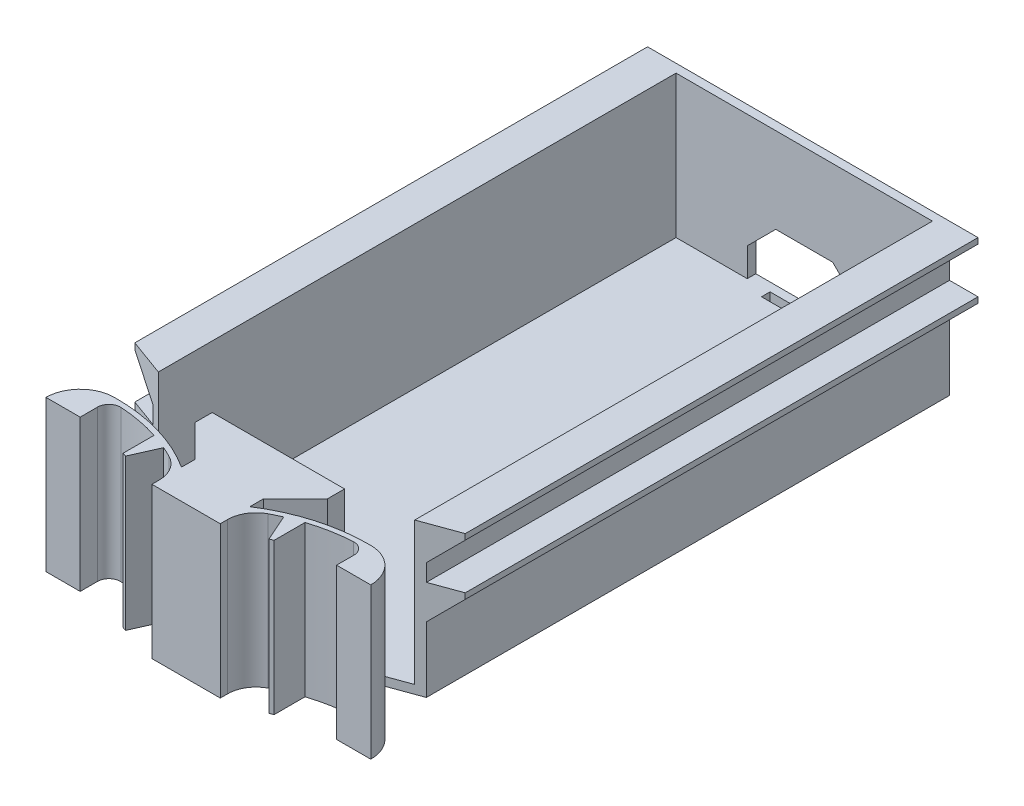
SolidWorks part; units mm, degrees
ref_plane "Plano frontal" through (0, 0, 0) normal (0, 0, 1) x (1, 0, 0)
ref_plane "Plano superior" through (0, 0, 0) normal (0, 1, 0) x (1, 0, 0)
ref_plane "Plano direito" through (0, 0, 0) normal (1, 0, 0) x (0, 0, -1)
sketch "Esboço1" plane through (0, 0, 0) normal (0, 0, 1) x (1, 0, 0)
  line L0 (-24, 14) -> (-24, -14) construction
  line L1 (24, 14) -> (24, -14) construction
  line L2 (-22.5, 12.5) -> (-22.5, -12.5)
  line L3 (-22.5, -12.5) -> (22.5, -12.5)
  line L4 (22.5, 12.5) -> (22.5, -12.5)
  line L5 (-22.5, 12.5) -> (22.5, -12.5) construction
  line L6 (-22.5, -12.5) -> (22.5, 12.5) construction
  line L7 (24, 12.5) -> (24, -14)
  line L8 (-24, -14) -> (24, -14)
  line L9 (-24, 12.5) -> (-24, -14)
  line L10 (-22.5, 12.5) -> (-24, 12.5)
  line L11 (22.5, 12.5) -> (24, 12.5)
  line L13 (-22.5, 12.5) -> (22.5, 12.5) construction
  line L14 (-24, 14) -> (24, 14) construction
  point P0 (0, 0)
  dimension "D1" = 25
  dimension "D2" = 45
  dimension "D3" = 1.5
extrude "Ressalto-extrusão1" add sketch "Esboço1" along normal blind 100
sketch "Esboço2" plane through (0, 0, 0) normal (0, 0, -1) x (-1, 0, 0)
  line L0 (-24, 12.5) -> (-29, 12.5)
  line L1 (-29, 11.5) -> (-24, 6.5)
  line L2 (-24, 12.5) -> (-24, 6.5)
  line L3 (-24, 6.5) -> (-24, 3.5) construction
  line L4 (-24, -14) -> (-24, 12.5) construction
  line L5 (-24, 3.5) -> (-29, 3.5)
  line L6 (-29, 2.5) -> (-24, -2.5)
  line L7 (-24, 3.5) -> (-24, -2.5)
  line L8 (0, -12.5) -> (0, 0) construction
  line L9 (-22.5, -12.5) -> (22.5, -12.5) construction
  line L10 (-24, 12.5) -> (-29, 12.5) construction
  line L11 (-29, 12.5) -> (-29, 11.5)
  line L12 (-29, 3.5) -> (-29, 2.5)
  line L13 (24, 12.5) -> (29, 12.5) construction
  line L14 (24, 6.5) -> (24, 3.5) construction
  line L15 (29, 3.5) -> (29, 2.5)
  line L16 (29, 12.5) -> (29, 11.5)
  line L17 (24, 3.5) -> (24, -2.5)
  line L18 (29, 2.5) -> (24, -2.5)
  line L19 (24, 3.5) -> (29, 3.5)
  line L20 (24, 12.5) -> (24, 6.5)
  line L21 (29, 11.5) -> (24, 6.5)
  line L22 (24, 12.5) -> (29, 12.5)
  dimension "D2" = 6
  dimension "D3" = 3
  dimension "D5" = 6
extrude "Ressalto-extrusão2" add sketch "Esboço2" against normal up to surface (100 mm away) up to face at (0, -0.375, 100)
sketch "Esboço3" plane through (0, -12.5, 0) normal (0, 1, 0) x (1, 0, 0)
  line L0 (22.5, -100) -> (22.5, 0) construction
  line L1 (-22.5, 0) -> (22.5, 0)
  line L2 (-22.5, 0) -> (-22.5, -1.5)
  line L3 (-22.5, -1.5) -> (22.5, -1.5)
  line L4 (22.5, 0) -> (22.5, -1.5)
  dimension "D1" = 1.5
extrude "Ressalto-extrusão3" add sketch "Esboço3" along normal up to surface (25 mm away) up to face at (-25.75, 12.5, 50)
sketch "Esboço4" plane through (0, 0, 1.5) normal (0, 0, 1) x (1, 0, 0)
  line L0 (22.5, -12.5) -> (-22.5, -12.5) construction
  line L1 (-10, -12.5) -> (10, -12.5)
  line L2 (-10, -12.5) -> (-10, -7.5)
  line L3 (-5, -2.5) -> (5, -2.5)
  line L4 (10, -12.5) -> (10, -7.5)
  line L5 (-10, -7.5) -> (-5, -2.5)
  line L6 (5, -2.5) -> (10, -7.5)
  point P1 (10, -2.5)
  point P2 (-10, -2.5)
  point P4 (0, -12.5)
  point P5 (0, -12.5)
extrude "Corte-extrusão1" cut sketch "Esboço4" against normal through all
sketch "Esboço5" plane through (0, -12.5, 0) normal (0, 1, 0) x (1, 0, 0)
  line L0 (0, 0) -> (0, -2.25) construction
  line L1 (22.5, -1.5) -> (-22.5, -1.5) construction
  line L2 (-6, -3) -> (6, -3)
  line L3 (-6, -3) -> (-6, -1.5)
  line L4 (-6, -1.5) -> (6, -1.5)
  line L5 (6, -3) -> (6, -1.5)
  line L6 (-6, -3) -> (6, -1.5) construction
  line L7 (-6, -1.5) -> (6, -3) construction
  dimension "D1" = 2.25
  dimension "D2" = 12
extrude "Corte-extrusão2" cut sketch "Esboço5" against normal through all
sketch "Esboço9" plane through (0, -14, 0) normal (0, -1, 0) x (1, 0, 0)
  line L0 (-12.5151, 96) -> (-29, 90)
  line L1 (29, 100) -> (29, 0) construction
  line L2 (29, 100) -> (29, 90)
  line L3 (29, 100) -> (12.5151, 100)
  line L4 (0, 100) -> (0, 80.1463) construction
  line L5 (-24, 100) -> (24, 100) construction
  line L6 (12.5151, 100) -> (12.5151, 96)
  line L7 (12.5151, 96) -> (29, 90)
  line L8 (-12.5151, 100) -> (-12.5151, 96)
  line L9 (-29, 100) -> (-12.5151, 100)
  line L10 (-29, 100) -> (-29, 90)
extrude "Corte-extrusão3" cut sketch "Esboço9" against normal through all
sketch "Esboço6" plane through (0, -14, 0) normal (0, -1, 0) x (1, 0, 0)
  line L0 (0, 93.7975) -> (0, 110) construction
  line L1 (-6, 110) -> (6, 110)
  line L2 (-11.6169, 93.7975) -> (11.6169, 93.7975)
  line L3 (6, 102.4144) -> (11.6169, 96.7975)
  line L4 (-22.5012, 106.0843) -> (-28.5012, 106.0843)
  line L5 (-22.5032, 103.0315) -> (-22.5012, 106.0843)
  line L6 (-22.5012, 105.1843) -> (-27.5212, 105.1843) construction
  line L7 (11.6169, 96.7975) -> (11.6169, 93.7975)
  line L8 (-6, 104.8102) -> (-6, 102.4144)
  line L9 (13.2473, 107.8029) -> (13.2473, 102.372)
  line L10 (12.6005, 108.0363) -> (10.5387, 103.397)
  line L11 (12.6005, 108.0363) -> (13.2473, 107.8029)
  line L12 (6, 110) -> (6, 108.7188)
  line L13 (6, 104.8102) -> (6, 102.4144)
  line L14 (-6, 110) -> (-6, 108.7188)
  line L15 (-12.6005, 108.0363) -> (-13.2473, 107.8029)
  line L16 (-12.6005, 108.0363) -> (-10.5387, 103.397)
  line L17 (-13.2473, 107.8029) -> (-13.2473, 102.372)
  line L18 (22.5032, 103.0315) -> (22.5012, 106.0843)
  line L19 (22.5012, 106.0843) -> (28.5012, 106.0843)
  line L26 (-11.6169, 96.7975) -> (-11.6169, 93.7975)
  line L27 (-6, 102.4144) -> (-11.6169, 96.7975)
  arc A0 (-28.5012, 106.0843) -> (-22.4128, 100.085) centre (-22.5012, 106.0843) ccw
  arc A1 (-22.4128, 100.085) -> (-6, 104.8102) centre (-22.0908, 129.834) ccw
  arc A2 (-10.5387, 103.397) -> (-8.6749, 104.2923) centre (-22.0908, 129.834) ccw
  arc A3 (-20.3849, 101.0337) -> (-13.2473, 102.372) centre (-22.0908, 129.834) ccw
  arc A4 (-27.5212, 105.1843) -> (-22.4149, 100.9851) centre (-22.5012, 106.0843) ccw construction
  arc A5 (-22.4149, 100.9851) -> (-0.6232, 110.5595) centre (-22.0908, 129.834) ccw construction
  arc A6 (-22.4128, 100.085) -> (0.0465, 109.9583) centre (-22.0908, 129.834) ccw construction
  arc A7 (-8.6749, 104.2923) -> (-6, 108.7188) centre (-11, 108.7188) ccw
  arc A8 (-22.5032, 103.0315) -> (-20.3849, 101.0337) centre (-20.5032, 103.0302) ccw
  arc A9 (22.5032, 103.0315) -> (20.3849, 101.0337) centre (20.5032, 103.0302) cw
  arc A10 (8.6749, 104.2923) -> (6, 108.7188) centre (11, 108.7188) cw
  arc A11 (20.3849, 101.0337) -> (13.2473, 102.372) centre (22.0908, 129.834) cw
  arc A12 (10.5387, 103.397) -> (8.6749, 104.2923) centre (22.0908, 129.834) cw
  arc A13 (22.4128, 100.085) -> (6, 104.8102) centre (22.0908, 129.834) cw
  arc A14 (28.5012, 106.0843) -> (22.4128, 100.085) centre (22.5012, 106.0843) cw
  point P54 (0, 93.7975)
  dimension "D3" = 0.9
  dimension "D5" = 5
  dimension "D6" = 2
  dimension "D2" = 6
extrude "Ressalto-extrusão10" add sketch "Esboço6" against normal through all
sketch "Esboço10" plane through (0, 12.5, 0) normal (0, 1, 0) x (1, 0, 0)
  line L1 (-41.2733, -88.7108) -> (41.2733, -88.7108)
  line L2 (-41.2733, -88.7108) -> (-41.2733, -117.1663)
  line L3 (-41.2733, -117.1663) -> (41.2733, -117.1663)
  line L4 (41.2733, -88.7108) -> (41.2733, -117.1663)
  line L5 (-41.2733, -88.7108) -> (41.2733, -117.1663) construction
  line L6 (-41.2733, -117.1663) -> (41.2733, -88.7108) construction
  line L7 (-55.6293, 33.3147) -> (55.6293, 33.3147)
  line L8 (-55.6293, 33.3147) -> (-55.6293, -130.7532)
  line L9 (-55.6293, -130.7532) -> (55.6293, -130.7532)
  line L10 (55.6293, 33.3147) -> (55.6293, -130.7532)
  line L11 (-55.6293, 33.3147) -> (55.6293, -130.7532) construction
  line L12 (-55.6293, -130.7532) -> (55.6293, 33.3147) construction
  point P0 (0, -102.9386)
  point P5 (0, -48.7192)
sketch "Esboço11" plane through (0, 12.5, 0) normal (0, 1, 0) x (1, 0, 0)
  line L0 (-35.1573, -99.4549) -> (-0.8414, -87.5949)
  line L1 (-0.8414, -87.5949) -> (34.9194, -102.7059)
  line L2 (34.9194, -102.7059) -> (33.8357, -115.1078)
  line L3 (33.8357, -115.1078) -> (-23.4779, -117.3353)
  line L4 (-23.4779, -117.3353) -> (-36.3614, -109.8701)
  line L5 (-36.3614, -109.8701) -> (-35.1573, -99.4549)
